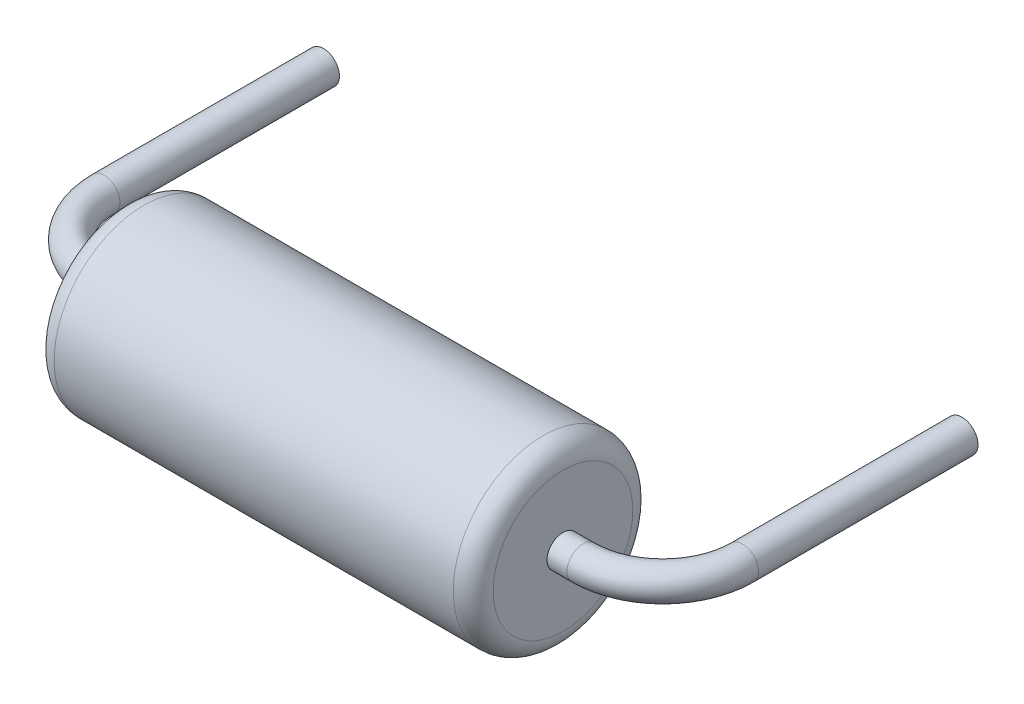
SolidWorks part; units mm, degrees
ref_plane "Front" through (0, 0, 0) normal (0, 0, 1) x (1, 0, 0)
ref_plane "Top" through (0, 0, 0) normal (0, 1, 0) x (1, 0, 0)
ref_plane "Right" through (0, 0, 0) normal (1, 0, 0) x (0, 0, -1)
sketch "Эскиз1" plane through (0, 0, 0) normal (0, 0, 1) x (1, 0, 0)
  line L1 (-1, -1) -> (1, -1)
  line L2 (-1, -1) -> (-1, 1)
  line L3 (-1, 1) -> (1, 1)
  line L4 (1, -1) -> (1, 1)
  line L5 (16, -1) -> (18, -1)
  line L6 (16, -1) -> (16, 1)
  line L7 (16, 1) -> (18, 1)
  line L8 (18, -1) -> (18, 1)
ref_plane "Плоскость1" through (2.5, 0, 0) normal (1, 0, 0) x (0, 0, -1)
sketch "Эскиз3" plane through (2.5, 0, 0) normal (1, 0, 0) x (0, 0, -1)
  line L0 (-2.25, 0) -> (0, 0) construction
  circle A0 centre (-2.25, 0) radius 2.25
  dimension "D1" = 4.5
extrude "Вытянуть1" add sketch "Эскиз3" along normal blind 11
ref_plane "Плоскость2" through (0, 0, -5.25) normal (0, 0, 1) x (1, 0, 0)
sketch "Эскиз4" plane through (0, 0, -5.25) normal (0, 0, 1) x (1, 0, 0)
  circle A0 centre (0, 0) radius 0.4
  dimension "D1" = 0.8
sketch "Эскиз5" plane through (0, 0, 0) normal (0, 1, 0) x (1, 0, 0)
  line L0 (0, 5.25) -> (0, -0.25)
  line L1 (2, -2.25) -> (2.9658, -2.25)
  line L2 (13.5, -2.25) -> (2.5, -2.25) construction
  line L3 (2.9658, -2.25) -> (14, -2.25)
  line L4 (8, 4.4274) -> (8, -6.3335) construction
  line L5 (16, 5.25) -> (16, -0.25)
  arc A0 (0, -0.25) -> (2, -2.25) centre (2, -0.25) ccw
  arc A1 (16, -0.25) -> (14, -2.25) centre (14, -0.25) cw
  point P14 (0, -2.25)
  point P17 (17, -2.25)
  dimension "D1" = 2
  dimension "D2" = 8
sweep "По траектории1" add profiles "Эскиз4" path "Эскиз5"
fillet "Скругление1" radius 0.5 2 edges at (2.5, 0, 0) (13.5, 0, 0)
